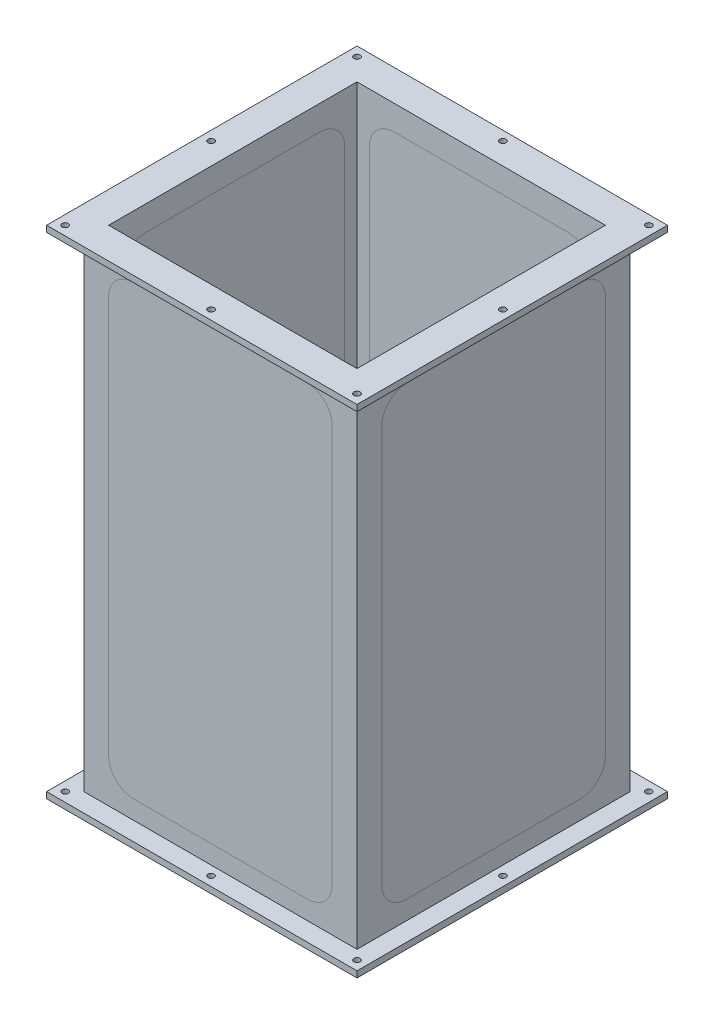
SolidWorks part; units mm, degrees
ref_plane "Front Plane" through (0, 0, 0) normal (0, 0, 1) x (1, 0, 0)
ref_plane "Top Plane" through (0, 0, 0) normal (0, 1, 0) x (1, 0, 0)
ref_plane "Right Plane" through (0, 0, 0) normal (1, 0, 0) x (0, 0, -1)
sketch "Sketch1" plane through (0, 0, 0) normal (0, 1, 0) x (1, 0, 0)
  line L0 (-100, -100) -> (100, -100)
  line L7 (-100, -100) -> (-100, 100)
  line L8 (100, -100) -> (100, 100)
  line L9 (-100, 100) -> (100, 100)
  line L10 (-100, -100) -> (100, 100) construction
  line L11 (100, -100) -> (-100, 100) construction
  line L12 (-110, 110) -> (110, 110)
  line L13 (110, -110) -> (110, 110)
  line L14 (-110, -110) -> (110, -110)
  line L15 (-110, -110) -> (-110, 110)
  point P1 (0, 0)
  dimension "D1" = 10
extrude "Boss-Extrude1" add sketch "Sketch1" along normal blind 400
sketch "Sketch2" plane through (0, 0, 110) normal (0, 0, 1) x (1, 0, 0)
  line L0 (0, 400) -> (0, 0) construction
  line L1 (-110, 400) -> (110, 400) construction
  line L3 (-70, 20) -> (70, 20)
  line L4 (-90, 40) -> (-90, 360)
  line L5 (-70, 380) -> (70, 380)
  line L6 (90, 40) -> (90, 360)
  line L7 (-90, 20) -> (90, 380) construction
  line L8 (-90, 380) -> (90, 20) construction
  arc A0 (-70, 20) -> (-90, 40) centre (-70, 40) cw
  arc A1 (70, 20) -> (90, 40) centre (70, 40) ccw
  arc A2 (-70, 380) -> (-90, 360) centre (-70, 360) ccw
  arc A3 (70, 380) -> (90, 360) centre (70, 360) cw
  point P5 (0, 200)
  dimension "D1" = 20
extrude "Cut-Extrude1" cut sketch "Sketch2" against normal blind 2000
sketch "Sketch3" plane through (110, 0, 0) normal (1, 0, 0) x (0, 0, -1)
  line L0 (-110, 400) -> (110, 0) construction
  line L2 (-70, 20) -> (70, 20)
  line L3 (-90, 40) -> (-90, 360)
  line L4 (-70, 380) -> (70, 380)
  line L5 (90, 40) -> (90, 360)
  line L6 (-90, 20) -> (90, 380) construction
  line L7 (-90, 380) -> (90, 20) construction
  arc A0 (70, 20) -> (90, 40) centre (70, 40) ccw
  arc A1 (-70, 20) -> (-90, 40) centre (-70, 40) cw
  arc A2 (-90, 360) -> (-70, 380) centre (-70, 360) cw
  arc A3 (70, 380) -> (90, 360) centre (70, 360) cw
  point P4 (0, 200)
  dimension "D1" = 20
extrude "Cut-Extrude2" cut sketch "Sketch3" against normal blind 2000
sketch "Sketch4" plane through (0, 0, 110) normal (0, 0, 1) x (1, 0, 0)
  line L0 (0, 400) -> (0, 0) construction
  line L2 (-110, 400) -> (110, 400) construction
  line L6 (-28.0001, 146.2253) -> (28.0001, 146.2253)
  line L8 (-28.0001, 146.2253) -> (-28.0001, 253.7747)
  line L9 (-28.0001, 253.7747) -> (28.0001, 253.7747)
  line L10 (28.0001, 146.2253) -> (28.0001, 253.7747)
  line L11 (-28.0001, 146.2253) -> (28.0001, 253.7747) construction
  line L12 (-28.0001, 253.7747) -> (28.0001, 146.2253) construction
  point P5 (0, 200)
sketch "Sketch5" plane through (0, 0, 110) normal (0, 0, 1) x (1, 0, 0)
  line L1 (-70, 20) -> (70, 20)
  line L2 (-90, 40) -> (-90, 360)
  line L3 (-70, 380) -> (70, 380)
  line L4 (90, 40) -> (90, 360)
  line L5 (-90, 20) -> (90, 380) construction
  line L6 (-90, 380) -> (90, 20) construction
  arc A0 (-70, 20) -> (-90, 40) centre (-70, 40) cw
  arc A1 (70, 20) -> (90, 40) centre (70, 40) ccw
  arc A2 (-90, 360) -> (-70, 380) centre (-70, 360) cw
  arc A3 (70, 380) -> (90, 360) centre (70, 360) cw
  point P0 (0, 200)
  dimension "D1" = 20
extrude "Boss-Extrude2" add sketch "Sketch5" against normal blind 10 separate body
ref_plane "Plane1" through (0, 0, 0) normal (0, 0, 1) x (1, 0, 0)
sketch "Sketch7" plane through (0, 0, 0) normal (0, 0, 1) x (1, 0, 0)
  line L0 (0, 400) -> (0, 0) construction
  point P4 (0, 200)
pattern_circular "CirPattern2" count 4 over 360 about axis through (0, 0, 0) along (0, 1, 0) of bodies 104
sketch "Sketch8" plane through (0, 400, 0) normal (0, 1, 0) x (1, 0, 0)
  line L0 (-125, 125) -> (125, 125)
  line L1 (-100, -100) -> (100, -100)
  line L2 (-100, -100) -> (-100, 100)
  line L3 (-100, 100) -> (100, 100)
  line L4 (100, -100) -> (100, 100)
  line L5 (-100, -100) -> (100, 100) construction
  line L6 (-100, 100) -> (100, -100) construction
  line L7 (125, -125) -> (125, 125)
  line L8 (-125, -125) -> (125, -125)
  line L9 (-125, -125) -> (-125, 125)
  line L10 (0, 110) -> (0, 125) construction
  line L11 (110, 110) -> (-110, 110) construction
  line L12 (-125, 125) -> (-110, 110) construction
  circle A0 centre (-117.5, 117.5) radius 2.5
  circle A1 centre (0, 117.5) radius 2.5
  circle A2 centre (117.5, 117.5) radius 2.5
  circle A3 centre (117.5, 0) radius 2.5
  circle A4 centre (117.5, -117.5) radius 2.5
  circle A5 centre (-117.5, 0) radius 2.5
  circle A6 centre (-117.5, -117.5) radius 2.5
  circle A7 centre (0, -117.5) radius 2.5
  point P0 (0, 0)
  dimension "D1" = 25
extrude "Boss-Extrude3" add sketch "Sketch8" against normal blind 5
ref_plane "Plane2" through (0, 200, 0) normal (0, 1, 0) x (1, 0, 0)
mirror "Mirror1" about plane through (0, 200, 0) normal (0, 1, 0) of "Boss-Extrude3"
